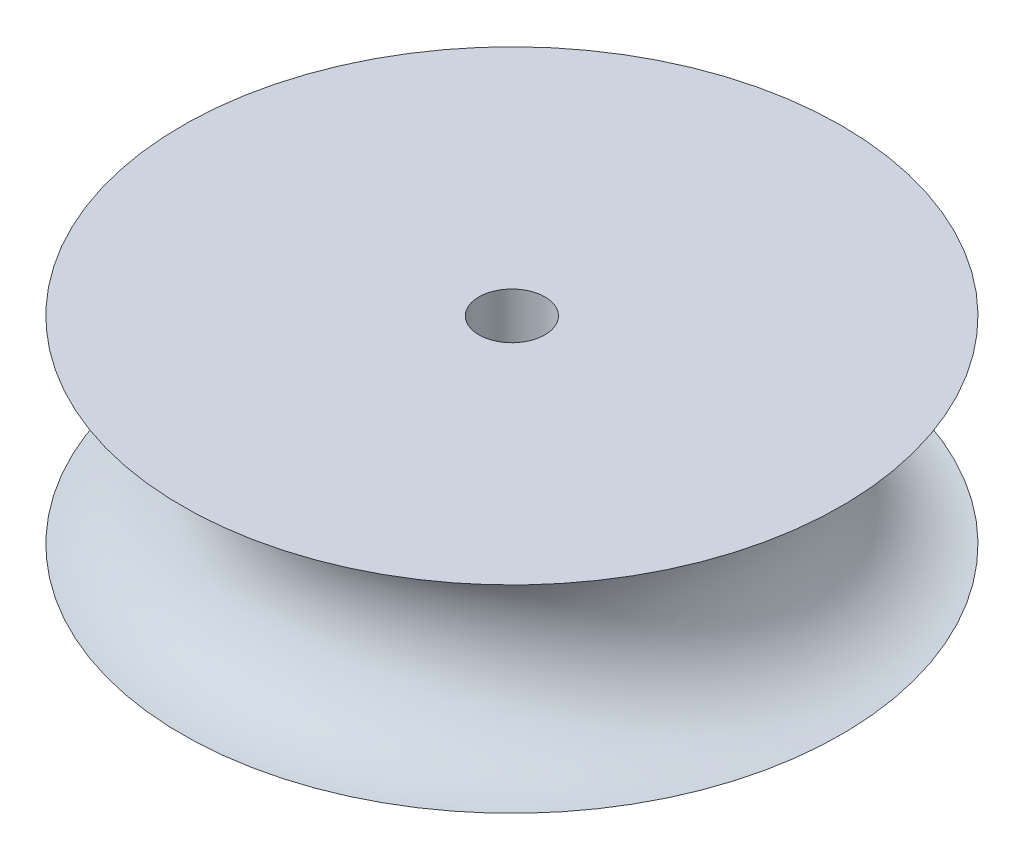
SolidWorks part; units mm, degrees
ref_plane "Front Plane" through (0, 0, 0) normal (0, 0, 1) x (1, 0, 0)
ref_plane "Top Plane" through (0, 0, 0) normal (0, 1, 0) x (1, 0, 0)
ref_plane "Right Plane" through (0, 0, 0) normal (1, 0, 0) x (0, 0, -1)
sketch "Sketch1" plane through (0, 0, 0) normal (0, 0, 1) x (1, 0, 0)
  line L0 (0, 0) -> (0, 30) construction
  line L1 (-5, 0) -> (-50, 0)
  line L2 (-5, 30) -> (-5, 0)
  line L3 (-50, 30) -> (-5, 30)
  arc A0 (-50, 0) -> (-50, 30) centre (-50, 15) ccw
  dimension "D2" = 30
  dimension "D1" = 30
  dimension "D3" = 50
  dimension "D4" = 5
revolve "Revolve1" add sketch "Sketch1" angle 360 about L0
